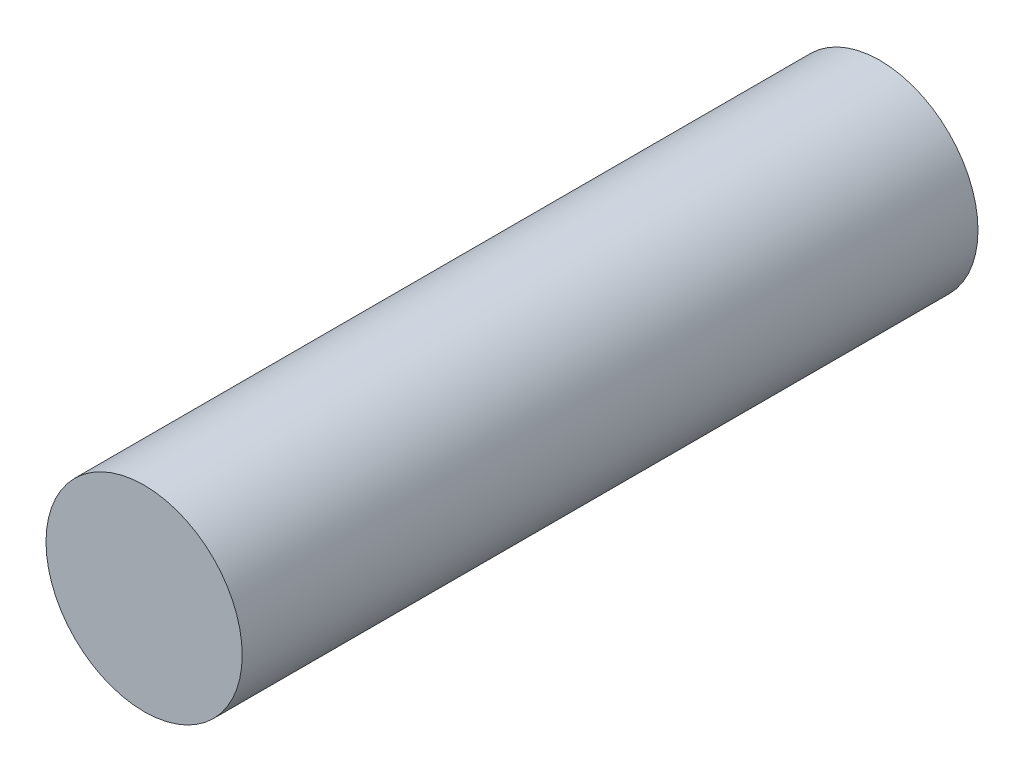
SolidWorks part; units mm, degrees
ref_plane "前视基准面" through (0, 0, 0) normal (0, 0, 1) x (1, 0, 0)
ref_plane "上视基准面" through (0, 0, 0) normal (0, 1, 0) x (1, 0, 0)
ref_plane "右视基准面" through (0, 0, 0) normal (1, 0, 0) x (0, 0, -1)
sketch "草图1" plane through (0, 0, 0) normal (0, 0, 1) x (1, 0, 0)
  circle A0 centre (0, 0) radius 10.16
extrude "凸台-拉伸1" add sketch "草图1" along normal blind 76.2
